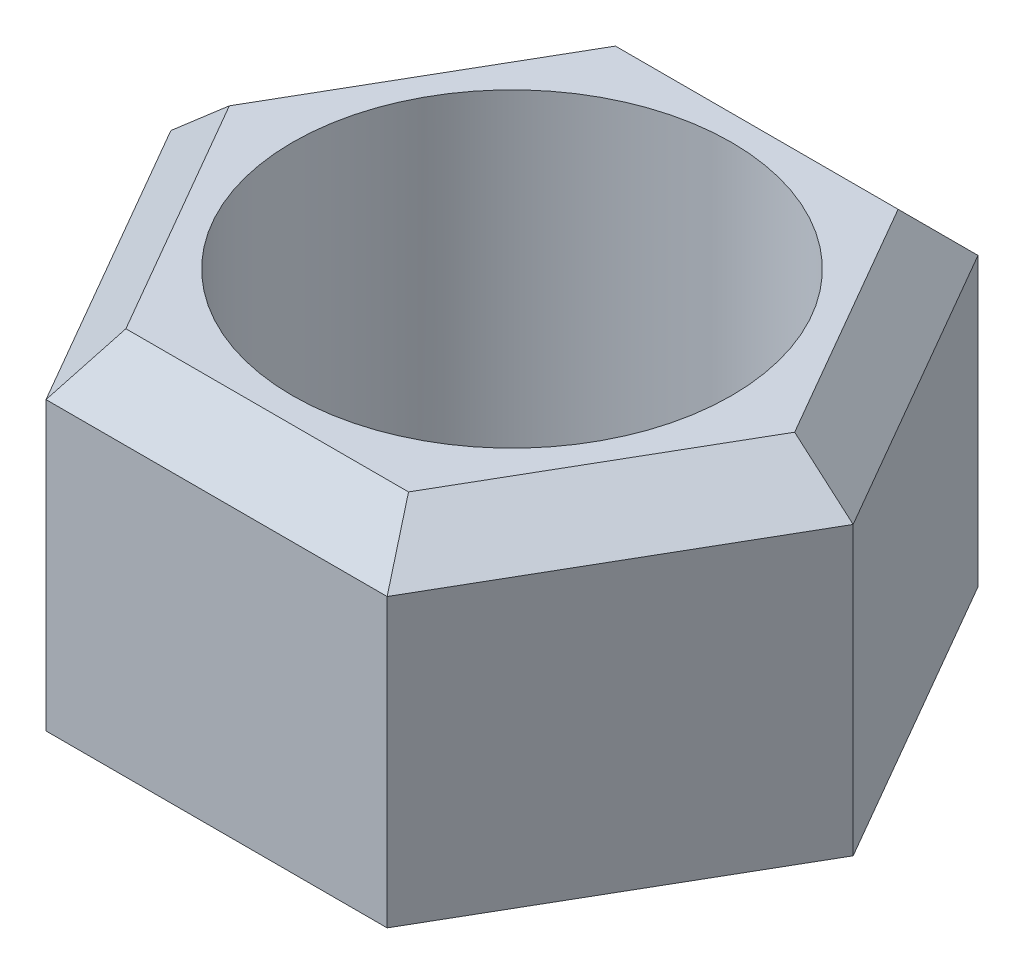
SolidWorks part; units mm, degrees
ref_plane "Front Plane" through (0, 0, 0) normal (0, 0, 1) x (1, 0, 0)
ref_plane "Top Plane" through (0, 0, 0) normal (0, 1, 0) x (1, 0, 0)
ref_plane "Right Plane" through (0, 0, 0) normal (1, 0, 0) x (0, 0, -1)
sketch "Sketch1" plane through (0, 0, 0) normal (0, 1, 0) x (1, 0, 0)
  line L1 (0.101, 0.175) -> (-0.101, 0.175)
  line L2 (-0.101, 0.175) -> (-0.2021, 0)
  line L3 (-0.2021, 0) -> (-0.101, -0.175)
  line L4 (-0.101, -0.175) -> (0.101, -0.175)
  line L5 (0.101, -0.175) -> (0.2021, 0)
  line L6 (0.2021, 0) -> (0.101, 0.175)
  circle A0 centre (0, 0) radius 0.175 construction
  dimension "D1" = 0.35
extrude "Boss-Extrude1" add sketch "Sketch1" along normal blind 0.2
sketch "Sketch3" plane through (0, 0, 0) normal (0, -1, 0) x (1, 0, 0)
  circle A0 centre (0, 0) radius 0.13
  dimension "D1" = 0.26
extrude "Cut-Extrude1" cut sketch "Sketch3" against normal up to next
chamfer "Chamfer2" distance 0.03 angle 45 6 edges at (0.1516, 0.2, 0.0875) (0, 0.2, 0.175) (-0.1516, 0.2, 0.0875) (-0.1516, 0.2, -0.0875) (0, 0.2, -0.175) (0.1516, 0.2, -0.0875)
